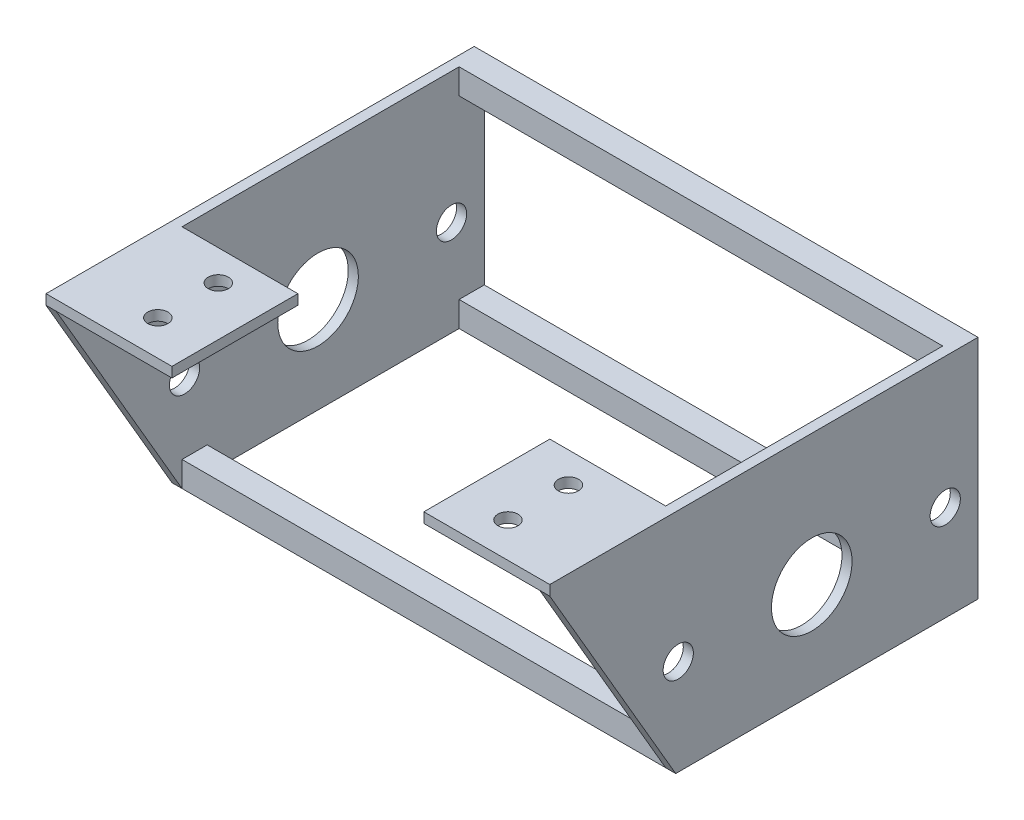
SolidWorks part; units mm, degrees
ref_plane "Front Plane" through (0, 0, 0) normal (0, 0, 1) x (1, 0, 0)
ref_plane "Top Plane" through (0, 0, 0) normal (0, 1, 0) x (1, 0, 0)
ref_plane "Right Plane" through (0, 0, 0) normal (1, 0, 0) x (0, 0, -1)
sketch "Sketch1" plane through (0, 0, 0) normal (0, 0, 1) x (1, 0, 0)
  line L9 (-50, 22.5) -> (50, 22.5)
  line L10 (-50, 22.5) -> (-50, -22.5)
  line L15 (-50, -22.5) -> (50, -22.5)
  line L16 (50, 22.5) -> (50, -22.5)
  line L17 (-50, 22.5) -> (50, -22.5) construction
  line L18 (-50, -22.5) -> (50, 22.5) construction
  point P0 (0, 0)
  dimension "D1" = 100
  dimension "D2" = 45
extrude "Boss-Extrude1" add sketch "Sketch1" along normal blind 90
sketch "Sketch2" plane through (-50, 0, 0) normal (-1, 0, 0) x (0, 0, 1)
  line L0 (60, -22.5) -> (85, 20.5)
  line L1 (90, 22.5) -> (90, -22.5)
  line L2 (90, -22.5) -> (60, -22.5)
  line L3 (90, -22.5) -> (0, -22.5) construction
  line L5 (85, 20.5) -> (85, 22.5)
  line L6 (90, 22.5) -> (0, 22.5) construction
  line L7 (85, 22.5) -> (90, 22.5)
  dimension "D1" = 2
  dimension "D2" = 5
extrude "Cut-Extrude1" cut sketch "Sketch2" against normal through all
sketch "Sketch3" plane through (0, 22.5, 0) normal (0, 1, 0) x (1, 0, 0)
  line L0 (0, 0) -> (0, -86.1628) construction
  line L1 (50, -86.1628) -> (-50, -86.1628) construction
  line L2 (50, 0) -> (-50, 0) construction
  line L3 (-48, -5) -> (48, -5)
  line L4 (-48, -5) -> (-48, -37.6387)
  line L5 (-48, -37.6387) -> (48, -37.6387)
  line L6 (48, -5) -> (48, -37.6387)
  line L7 (-48, -5) -> (48, -37.6387) construction
  line L8 (-48, -37.6387) -> (48, -5) construction
  line L9 (50, -85) -> (50, 0) construction
  point P5 (0, -21.3193)
  dimension "D1" = 2
  dimension "D2" = 5
extrude "Cut-Extrude2" cut sketch "Sketch3" against normal through all both and the other way through all
sketch "Sketch4" plane through (0, 0, 0) normal (0, 0, -1) x (-1, 0, 0)
  line L0 (50, 22.5) -> (50, -22.5) construction
  line L1 (-48, 17.5) -> (48, 17.5)
  line L2 (-48, 17.5) -> (-48, -17.5)
  line L3 (-48, -17.5) -> (48, -17.5)
  line L4 (48, 17.5) -> (48, -17.5)
  line L5 (-48, 17.5) -> (48, -17.5) construction
  line L6 (-48, -17.5) -> (48, 17.5) construction
  line L7 (-50, 22.5) -> (50, 22.5) construction
  point P0 (0, 0)
  dimension "D1" = 2
  dimension "D2" = 5
extrude "Cut-Extrude4" cut sketch "Sketch4" against normal through all
sketch "Sketch5" plane through (50, 0, 0) normal (1, 0, 0) x (0, 0, -1)
  line L0 (-85, 22.5) -> (0, 22.5) construction
  line L2 (0, -22.5) -> (0, 22.5) construction
  line L3 (2.1436, -3.5) -> (-62.8328, -3.5) construction
  line L4 (-33, -3.5) -> (-6.5, -3.5) construction
  circle A0 centre (-33, -3.5) radius 8
  circle A1 centre (-6.5, -3.5) radius 3
  circle A2 centre (-59.5, -3.5) radius 3
  dimension "D1" = 16
  dimension "D8" = 6
  dimension "D9" = 6
  dimension "D2" = 26
  dimension "D3" = 53
  dimension "D4" = 26.5
  dimension "D5" = 33
  dimension "D6" = 26.5
  dimension "D7" = 0
extrude "Cut-Extrude5" cut sketch "Sketch5" against normal through all
sketch "Sketch7" plane through (0, 0, 37.6387) normal (0, 0, -1) x (-1, 0, 0)
  line L0 (48, 17.5) -> (48, 22.5) construction
  line L1 (-48, 17.5) -> (48, 17.5)
  line L2 (-48, 17.5) -> (-48, 20.5)
  line L3 (-48, 20.5) -> (48, 20.5)
  line L4 (48, 17.5) -> (48, 20.5)
  dimension "D1" = 3
extrude "Cut-Extrude7" cut sketch "Sketch7" against normal through all
sketch "Sketch8" plane through (0, -22.5, 0) normal (0, -1, 0) x (1, 0, 0)
  line L0 (50, 60) -> (-50, 60) construction
  line L2 (-48, 51.8741) -> (-48, 37.6387)
  line L3 (-48, 37.6387) -> (48, 37.6387)
  line L4 (48, 51.8741) -> (48, 37.6387)
  line L5 (-48, 37.6387) -> (48, 37.6387) construction
  line L7 (48, 37.6387) -> (48, 5) construction
  line L9 (48, 51.8741) -> (48, 55)
  line L10 (48, 55) -> (-48, 55)
  line L11 (-48, 51.8741) -> (-48, 55)
  line L12 (-48, 5) -> (-48, 37.6387) construction
  dimension "D1" = 5
sketch "Sketch9" plane through (0, 20.5, 0) normal (0, -1, 0) x (1, 0, 0)
  line L1 (-25, 88.839) -> (25, 88.839)
  line L2 (-25, 88.839) -> (-25, 29.7441)
  line L3 (-25, 29.7441) -> (25, 29.7441)
  line L4 (25, 88.839) -> (25, 29.7441)
  line L5 (-25, 88.839) -> (25, 29.7441) construction
  line L6 (-25, 29.7441) -> (25, 88.839) construction
  point P0 (0, 59.2915)
  point P7 (0, 58.9663)
  point P8 (0, 59.2915)
  dimension "D1" = 50
extrude "Cut-Extrude9" cut sketch "Sketch9" against normal blind 34
sketch "Sketch10" plane through (0, 20.5, 0) normal (0, -1, 0) x (1, 0, 0)
  line L0 (25, 85) -> (48, 85) construction
  line L1 (0, 103.5883) -> (0, -36.9658) construction
  circle A0 centre (34.75, 78.05) radius 2
  circle A1 centre (34.75, 66.05) radius 2
  circle A2 centre (-34.75, 66.05) radius 2
  circle A3 centre (-34.75, 78.05) radius 2
  dimension "D1" = 4
  dimension "D2" = 4
  dimension "D3" = 12
  dimension "D4" = 6.95
extrude "Cut-Extrude10" cut sketch "Sketch10" against normal blind 34
extrude "Cut-Extrude11" cut sketch "Sketch8" against normal through all
sketch "Sketch11" plane through (0, -22.5, 0) normal (0, -1, 0) x (1, 0, 0)
  line L0 (50, 60) -> (-50, 60) construction
  line L1 (-48, 60) -> (48, 60)
  line L2 (-48, 60) -> (-48, 66.4751)
  line L3 (-48, 66.4751) -> (48, 66.4751)
  line L4 (48, 60) -> (48, 66.4751)
  line L5 (0, 16.3331) -> (0, 82.3716) construction
  point P9 (0, 66.4751)
  dimension "D1" = 96
extrude "Cut-Extrude12" cut sketch "Sketch11" against normal blind 34
sketch "Sketch12" plane through (0, 20.5, 0) normal (0, -1, 0) x (1, 0, 0)
  line L0 (0, 83.4134) -> (0, -15.1979) construction
  line L1 (-25, 55) -> (-25, 85) construction
  line L2 (-48, 33.0757) -> (-25, 33.0757)
  line L3 (-48, 33.0757) -> (-48, 60)
  line L4 (-48, 60) -> (-25, 60)
  line L5 (-25, 33.0757) -> (-25, 60)
  line L6 (25, 33.0757) -> (25, 60)
  line L7 (48, 60) -> (25, 60)
  line L8 (48, 33.0757) -> (48, 60)
  line L9 (48, 33.0757) -> (25, 33.0757)
  line L10 (-48, 85) -> (-48, 55) construction
extrude "Cut-Extrude13" cut sketch "Sketch12" against normal blind 34
